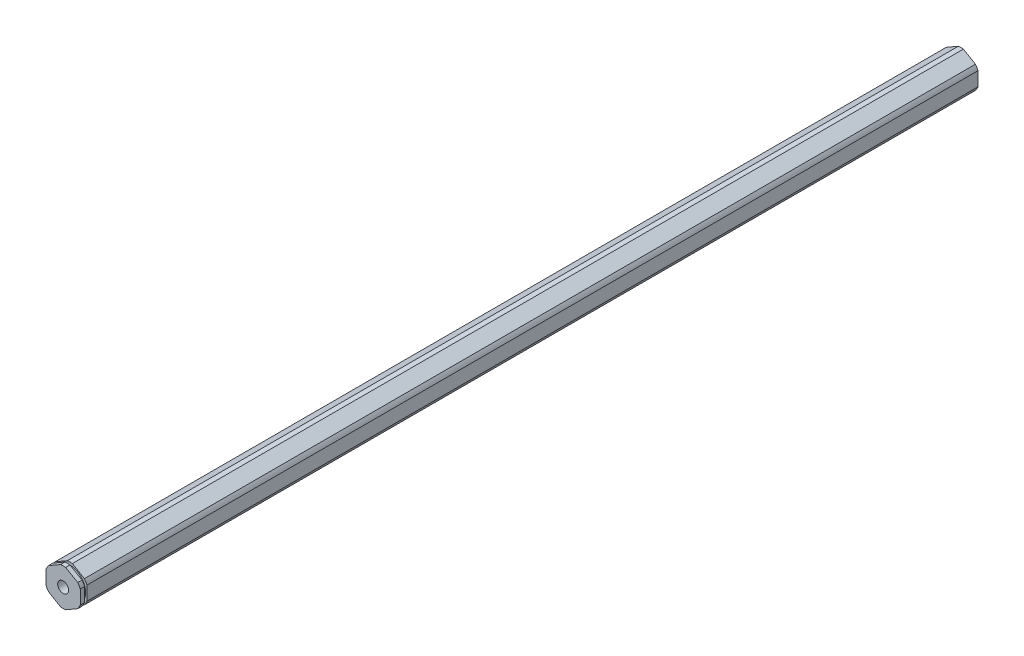
SolidWorks part; units mm, degrees
ref_plane "Front Plane" through (0, 0, 0) normal (0, 0, 1) x (1, 0, 0)
ref_plane "Top Plane" through (0, 0, 0) normal (0, 1, 0) x (1, 0, 0)
ref_plane "Right Plane" through (0, 0, 0) normal (1, 0, 0) x (0, 0, -1)
sketch "Sketch1" plane through (0, 0, 0) normal (0, 0, 1) x (1, 0, 0)
  line L1 (0, 7.3323) -> (-6.35, 3.6662)
  line L2 (-6.35, 3.6662) -> (-6.35, -3.6662)
  line L3 (-6.35, -3.6662) -> (0, -7.3323)
  line L4 (0, -7.3323) -> (6.35, -3.6662)
  line L5 (6.35, -3.6662) -> (6.35, 3.6662)
  line L6 (6.35, 3.6662) -> (0, 7.3323)
  circle A0 centre (0, 0) radius 6.35 construction
  circle A1 centre (0, 0) radius 6.858
  dimension "D1" = 12.7
  dimension "D2" = 13.716
extrude "Boss-Extrude1" add sketch "Sketch1" along normal mid plane 332.6765 contours L5 A1 L6 L1 L2 L3 L4
hole_wizard "#10-32 Tapped Hole1" positions "3DSketch1" profile "Sketch2" tap size "#10-32" standard "ANSI Inch"
sketch3d "3DSketch1"
  line L0 (0, 0, 166.3382) -> (0, 0, -166.3382) construction
  line L1 (0, 0, 166.3382) -> (0, 0, -166.3382) construction
  point P0 (0, 0, 166.3382)
  point P4 (0, 0, -166.3382)
sketch "Sketch2" plane through (0, 0, 166.3382) normal (1, 0, 0) x (0, -1, 0)
  line L0 (0, 0) -> (0, 17.5608)
  line L1 (0, 17.5608) -> (2.0193, 16.3474)
  line L2 (2.0193, 16.3474) -> (2.0193, 0)
  line L5 (2.0193, 0) -> (0, 0)
  line L10 (0, 17.5608) -> (-2.0193, 16.3474) construction
  line L11 (0, -6.35) -> (0, 107.95) construction
  dimension "Tap Drill Dia." = 4.0386
  dimension "Tap Drill Depth" = 16.3474
  dimension "Drill Angle" = 118
cosmetic thread "Hole Thread1" parameters "D1"=13.97, "D2"=4.826
cosmetic thread "Hole Thread2" parameters "D1"=13.97, "D2"=4.826
sketch "Sketch5" plane through (0, 0, 0) normal (1, 0, 0) x (0, 0, -1)
  line L0 (166.3382, 6.858) -> (-166.3382, 6.858) construction
  line L1 (-164.7507, 6.858) -> (-163.8618, 6.858)
  line L2 (-164.7507, 6.858) -> (-164.7508, 5.8547)
  line L3 (-164.7508, 5.8547) -> (-163.8618, 5.8547)
  line L4 (-163.8618, 6.858) -> (-163.8618, 5.8547)
  line L5 (-165.0472, 0) -> (-158.8423, 0) construction
  dimension "D1" = 5.8547
  dimension "D2" = 0.889
  dimension "D3" = 1.5875
revolve "Cut-Revolve1" cut sketch "Sketch5" angle 360 about L5
mirror "Mirror1" [suppressed] about plane through (0, 0, 0) normal (0, 0, 1)
